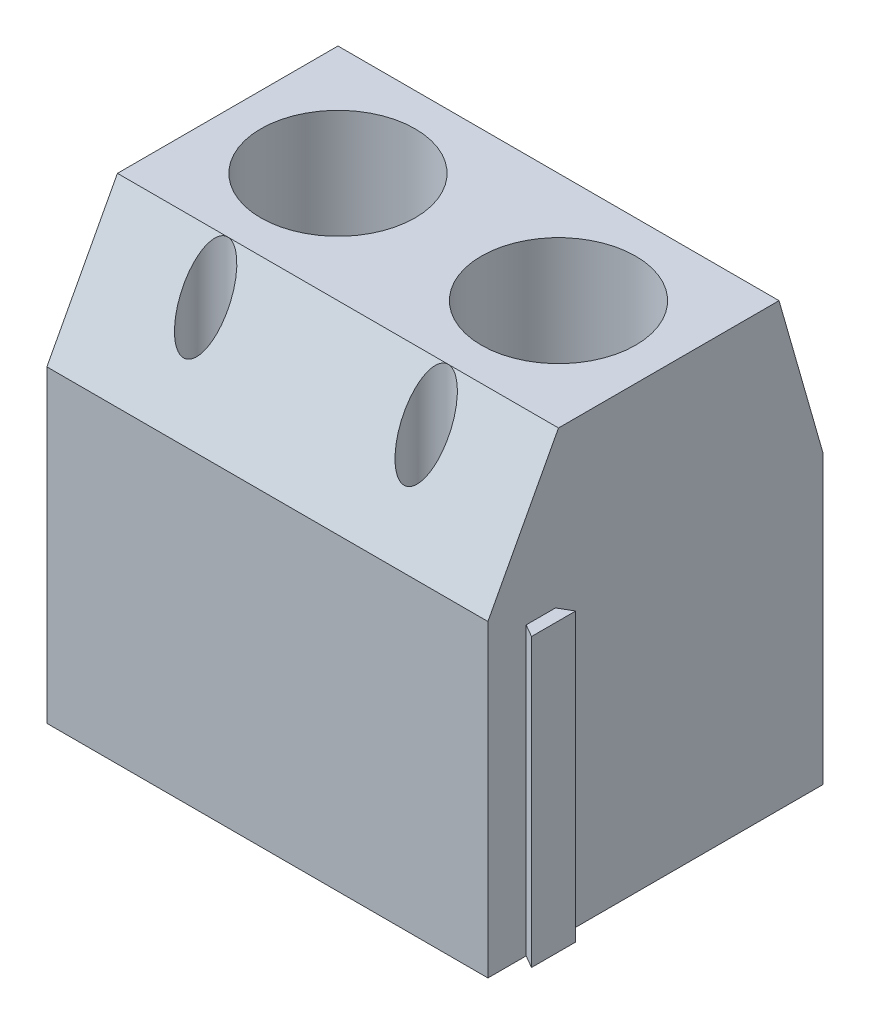
SolidWorks part; units mm, degrees
ref_plane "Front Plane" through (0, 0, 0) normal (0, 0, 1) x (1, 0, 0)
ref_plane "Top Plane" through (0, 0, 0) normal (0, 1, 0) x (1, 0, 0)
ref_plane "Right Plane" through (0, 0, 0) normal (1, 0, 0) x (0, 0, -1)
sketch "Sketch1" plane through (0, 0, 0) normal (0, 1, 0) x (1, 0, 0)
  line L0 (-4.7482, 3.126) -> (-4.7482, 3.9332)
  line L1 (-4.7482, -3.6668) -> (5.2518, -3.6668)
  line L2 (-4.7482, -3.6668) -> (-4.7482, -2.8002)
  line L3 (-4.7482, 3.9332) -> (5.0605, 3.9332)
  line L4 (5.2518, -3.6668) -> (5.2518, -2.8002)
  line L5 (5.0605, 3.9332) -> (5.2518, 3.9332)
  line L6 (-4.7482, 3.126) -> (-4.7482, 1.7404)
  line L7 (5.2518, 2.9928) -> (5.2518, 1.6072)
  line L8 (-4.7482, -2.1335) -> (-4.7482, 1.7404)
  line L9 (-4.7482, -2.8002) -> (-4.4595, -2.9668)
  line L10 (-4.4595, -2.9668) -> (-4.4595, -1.9668)
  line L11 (-4.4595, -1.9668) -> (-4.7482, -2.1335)
  line L12 (5.2518, -2.8002) -> (5.5405, -2.9668)
  line L13 (5.2518, 2.9928) -> (5.2518, 3.9332)
  line L14 (5.5405, -2.9668) -> (5.5405, -1.9668)
  line L15 (5.5405, -1.9668) -> (5.2518, -2.1335)
  line L16 (5.2518, -2.1335) -> (5.2518, 1.6072)
  point P0 (0, 0)
  dimension "D1" = 10
  dimension "D2" = 7.6
  dimension "D3" = 1
  dimension "D5" = 1
extrude "Boss-Extrude1" add sketch "Sketch1" along normal blind 6.5
sketch "Sketch2" plane through (0, 0, -3.9332) normal (0, 0, -1) x (-1, 0, 0)
  line L0 (-5.2518, 6.5) -> (4.7482, 6.5) construction
  line L1 (-4.7518, 0.5) -> (-0.7518, 0.5)
  line L2 (-4.7518, 0.5) -> (-4.7518, 5.5)
  line L3 (-4.7518, 5.5) -> (-0.7518, 5.5)
  line L4 (-0.7518, 0.5) -> (-0.7518, 5.5)
  line L5 (-4.7518, 0.5) -> (-0.7518, 5.5) construction
  line L6 (-4.7518, 5.5) -> (-0.7518, 0.5) construction
  line L7 (-5.2518, 6.5) -> (-5.2518, 0) construction
  line L9 (0.2482, 0.5) -> (4.2482, 0.5)
  line L10 (0.2482, 0.5) -> (0.2482, 5.5)
  line L11 (0.2482, 5.5) -> (4.2482, 5.5)
  line L12 (4.2482, 0.5) -> (4.2482, 5.5)
  line L13 (0.2482, 0.5) -> (4.2482, 5.5) construction
  line L14 (0.2482, 5.5) -> (4.2482, 0.5) construction
  point P0 (-2.7518, 3)
  point P9 (2.2482, 3)
  dimension "D1" = 4
  dimension "D2" = 5
  dimension "D3" = 1
  dimension "D4" = 0.5
  dimension "D5" = 4
  dimension "D6" = 5
  dimension "D7" = 1
  dimension "D8" = 1
extrude "Cut-Extrude1" cut sketch "Sketch2" against normal blind 7
sketch "Sketch3" plane through (0, 0, 0) normal (0, -1, 0) x (-1, 0, 0)
  line L0 (-5.2518, 3.9332) -> (4.7482, 3.9332) construction
  line L1 (-3.25, 3.9332) -> (-2.25, 3.9332)
  line L2 (-3.25, 3.9332) -> (-3.25, -0.5768)
  line L3 (-2.76, -1.0668) -> (-2.74, -1.0668)
  line L4 (-2.25, 3.9332) -> (-2.25, -0.5768)
  line L5 (-3.25, 3.9332) -> (-2.25, -1.0668) construction
  line L6 (-3.25, -1.0668) -> (-2.25, 3.9332) construction
  line L8 (1.75, 3.9332) -> (2.75, 3.9332)
  line L9 (1.75, 3.9332) -> (1.75, -0.5768)
  line L10 (2.24, -1.0668) -> (2.26, -1.0668)
  line L11 (2.75, 3.9332) -> (2.75, -0.5768)
  line L12 (1.75, 3.9332) -> (2.75, -1.0668) construction
  line L13 (1.75, -1.0668) -> (2.75, 3.9332) construction
  arc A0 (-2.74, -1.0668) -> (-2.25, -0.5768) centre (-2.74, -0.5768) ccw
  arc A1 (-3.25, -0.5768) -> (-2.76, -1.0668) centre (-2.76, -0.5768) ccw
  arc A2 (2.26, -1.0668) -> (2.75, -0.5768) centre (2.26, -0.5768) ccw
  arc A3 (1.75, -0.5768) -> (2.24, -1.0668) centre (2.24, -0.5768) ccw
  point P0 (-2.75, 1.4332)
  point P14 (2.25, 1.4332)
  dimension "D5" = 0.49
  dimension "D10" = 0.49
  dimension "D1" = 5
  dimension "D2" = 1
  dimension "D3" = 2.75
  dimension "D4" = 0
  dimension "D6" = 5
  dimension "D7" = 1
  dimension "D8" = 0
  dimension "D9" = 2.25
extrude "Cut-Extrude2" cut sketch "Sketch3" against normal blind 0.5
sketch "Sketch4" plane through (5.2518, 0, 0) normal (1, 0, 0) x (0, 0, -1)
  line L0 (3.9332, 6.5) -> (-3.6668, 6.5)
  line L1 (-3.6668, 6.5) -> (-3.6668, 7)
  line L2 (-3.6668, 7) -> (-2.0668, 10)
  line L3 (-2.0668, 10) -> (2.9332, 10)
  line L4 (2.9332, 10) -> (3.9332, 6.5)
  dimension "D1" = 3.5
  dimension "D2" = 5
  dimension "D3" = 1
  dimension "D4" = 0.5
  dimension "D5" = 3
extrude "Boss-Extrude2" add sketch "Sketch4" against normal blind 10
sketch "Sketch5" plane through (0, 10, 0) normal (0, 1, 0) x (1, 0, 0)
  line L0 (5.2518, 3.9332) -> (-4.7482, 3.9332) construction
  line L1 (-4.7482, 2.9332) -> (-4.7482, -2.0668) construction
  line L2 (5.2518, 2.9332) -> (5.2518, -2.0668) construction
  line L3 (-4.7482, -2.0668) -> (5.2518, -2.0668) construction
  line L4 (-4.7482, -2.0668) -> (-4.7482, -3.6668) construction
  line L5 (5.2518, -2.0668) -> (5.2518, -3.6668) construction
  circle A0 centre (-2.2482, 0.4332) radius 1.75
  circle A1 centre (2.7518, 0.4332) radius 1.75
  circle A2 centre (-2.2482, -2.5668) radius 0.5
  circle A3 centre (2.7518, -2.5668) radius 0.5
  dimension "D1" = 3.5
  dimension "D3" = 3.5
  dimension "D6" = 3.5
  dimension "D7" = 1
  dimension "D8" = 1
  dimension "D2" = 2.5
  dimension "D4" = 3.5
  dimension "D5" = 2.5
  dimension "D9" = 0.5
  dimension "D10" = 0.5
  dimension "D11" = 2.5
  dimension "D12" = 2.5
extrude "Cut-Extrude3" cut sketch "Sketch5" against normal blind 3.5
sketch "Sketch7" plane through (0, 6.5, 0) normal (0, 1, 0) x (1, 0, 0)
  line L0 (5.2518, 3.9332) -> (-4.7482, 3.9332) construction
  line L1 (5.2518, 2.9332) -> (5.2518, -2.0668) construction
  circle A0 centre (-2.25, 0.4332) radius 1
  circle A1 centre (2.7518, 0.4332) radius 1
  dimension "D1" = 3.5
  dimension "D3" = 2
  dimension "D2" = 2.25
  dimension "D4" = 2.5
  dimension "D5" = 3.5
extrude "Cut-Extrude4" cut sketch "Sketch7" against normal blind 1
